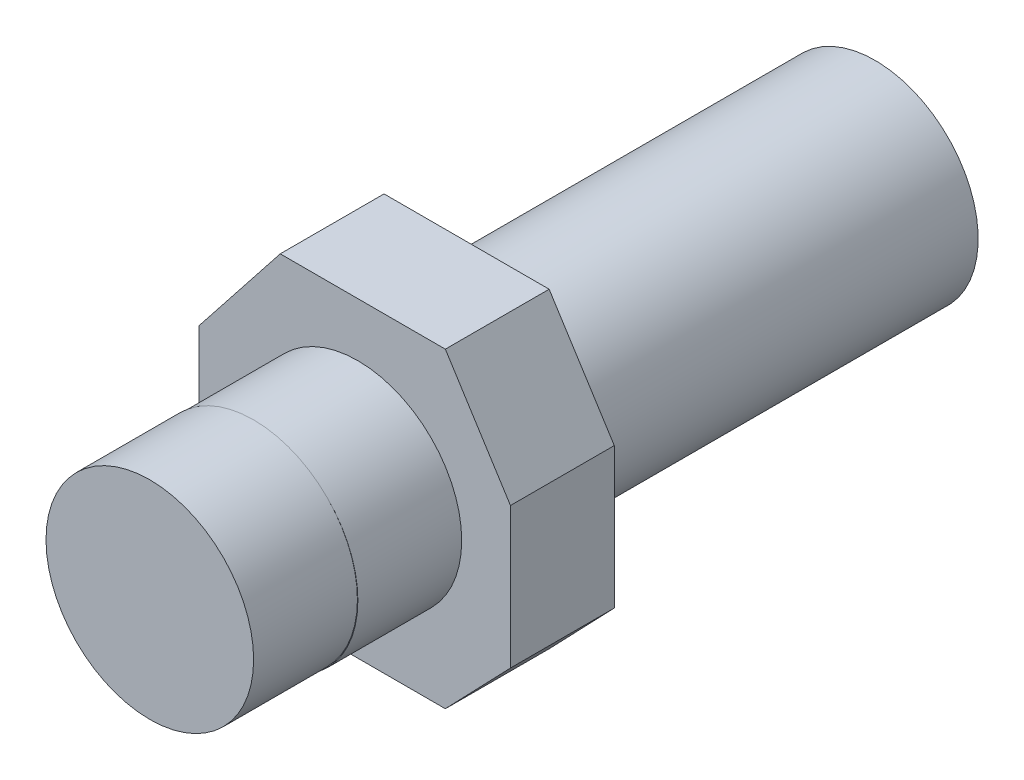
SolidWorks part; units mm, degrees
ref_plane "Front Plane" through (0, 0, 0) normal (0, 0, 1) x (1, 0, 0)
ref_plane "Top Plane" through (0, 0, 0) normal (0, 1, 0) x (1, 0, 0)
ref_plane "Right Plane" through (0, 0, 0) normal (1, 0, 0) x (0, 0, -1)
sketch "Sketch1" plane through (0, 0, 0) normal (0, 0, 1) x (1, 0, 0)
  line L4 (3.2151, 16.1664) -> (19.1208, 16.1664)
  line L5 (19.1208, 16.1664) -> (25.3926, 6.258)
  line L6 (25.3926, 6.258) -> (25.3926, -7.301)
  line L7 (25.3926, -7.301) -> (19.1208, -13.8336)
  line L8 (19.1208, -13.8336) -> (3.2151, -13.8336)
  line L9 (3.2151, -13.8336) -> (-4.6074, -7.301)
  line L10 (-4.6074, -7.301) -> (-4.6074, 6.258)
  line L11 (-4.6074, 6.258) -> (3.2151, 16.1664)
extrude "Boss-Extrude1" add sketch "Sketch1" along normal blind 10
sketch "Sketch2" plane through (0, 0, 10) normal (0, 0, 1) x (1, 0, 0)
  circle A0 centre (10.6959, 0.9932) radius 10
extrude "Boss-Extrude2" add sketch "Sketch2" along normal blind 10
sketch "Sketch3" plane through (0, 0, 20) normal (0, 0, 1) x (1, 0, 0)
  circle A0 centre (10.6525, 1.0365) radius 10
extrude "Boss-Extrude3" add sketch "Sketch3" along normal blind 10 contours A0
sketch "Sketch4" plane through (0, 0, 0) normal (0, 0, -1) x (-1, 0, 0)
  circle A0 centre (-10.5226, 1.0365) radius 9.925
extrude "Boss-Extrude4" add sketch "Sketch4" along normal blind 40
